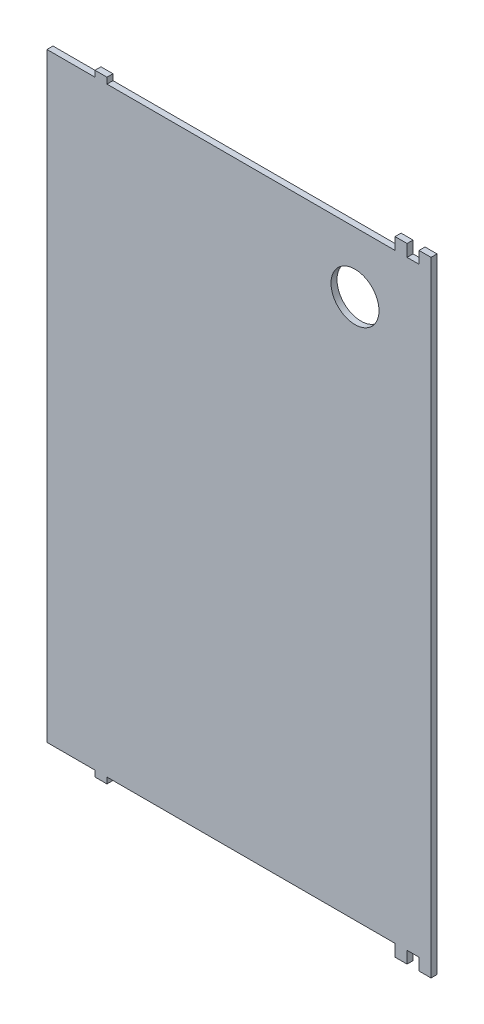
SolidWorks part; units mm, degrees
ref_plane "前视基准面" through (0, 0, 0) normal (0, 0, 1) x (1, 0, 0)
ref_plane "上视基准面" through (0, 0, 0) normal (0, 1, 0) x (1, 0, 0)
ref_plane "右视基准面" through (0, 0, 0) normal (1, 0, 0) x (0, 0, -1)
sketch "草图1" plane through (0, 0, 0) normal (0, 0, 1) x (1, 0, 0)
  line L10 (43.6314, -53.1099) -> (43.6314, -57.1099)
  line L11 (43.6314, -57.1099) -> (39.6314, -57.1099)
  line L12 (39.6314, -57.1099) -> (39.6314, -53.1099)
  line L13 (39.6314, -53.1099) -> (35.6314, -53.1099)
  line L14 (35.6314, -53.1099) -> (35.6314, -57.1099)
  line L15 (35.6314, -57.1099) -> (31.6314, -57.1099)
  line L16 (31.6314, -57.1099) -> (31.6314, -53.1099)
  line L18 (43.6314, -53.1099) -> (43.6314, 146.8901)
  line L19 (-84.3686, 146.8901) -> (-84.3686, -53.1099)
  line L21 (43.6314, 46.8901) -> (-84.3686, 46.8901) construction
  line L23 (31.6314, 150.8901) -> (31.6314, 146.8901)
  line L24 (35.6314, 150.8901) -> (31.6314, 150.8901)
  line L25 (35.6314, 146.8901) -> (35.6314, 150.8901)
  line L26 (39.6314, 146.8901) -> (35.6314, 146.8901)
  line L27 (39.6314, 150.8901) -> (39.6314, 146.8901)
  line L28 (43.6314, 150.8901) -> (39.6314, 150.8901)
  line L29 (43.6314, 146.8901) -> (43.6314, 150.8901)
  line L30 (33.6314, 150.8901) -> (33.6314, 146.8901) construction
  line L31 (33.6314, 146.8901) -> (-66.3686, 146.8901) construction
  line L32 (-66.3686, 146.8901) -> (-66.3686, 148.8901) construction
  line L33 (-66.3686, 148.8901) -> (-64.3686, 148.8901)
  line L34 (-64.3686, 148.8901) -> (-64.3686, 146.8901)
  line L35 (-66.3686, 148.8901) -> (-68.3686, 148.8901)
  line L36 (-68.3686, 148.8901) -> (-68.3686, 146.8901)
  line L37 (-68.3686, 146.8901) -> (-84.3686, 146.8901)
  line L38 (-64.3686, 146.8901) -> (31.6314, 146.8901)
  line L39 (-68.3686, -53.1099) -> (-84.3686, -53.1099)
  line L40 (-66.3686, -55.1099) -> (-68.3686, -55.1099)
  line L41 (-66.3686, -55.1099) -> (-64.3686, -55.1099)
  line L42 (-64.3686, -55.1099) -> (-64.3686, -53.1099)
  line L43 (-64.3686, -53.1099) -> (31.6314, -53.1099)
  line L44 (-68.3686, -53.1099) -> (-68.3686, -55.1099)
  circle A0 centre (18.2892, 126.8034) radius 8
  dimension "D1" = 116
  dimension "D2" = 4
  dimension "D3" = 4
  dimension "D4" = 4
extrude "凸台-拉伸1" add sketch "草图1" along normal blind 2
